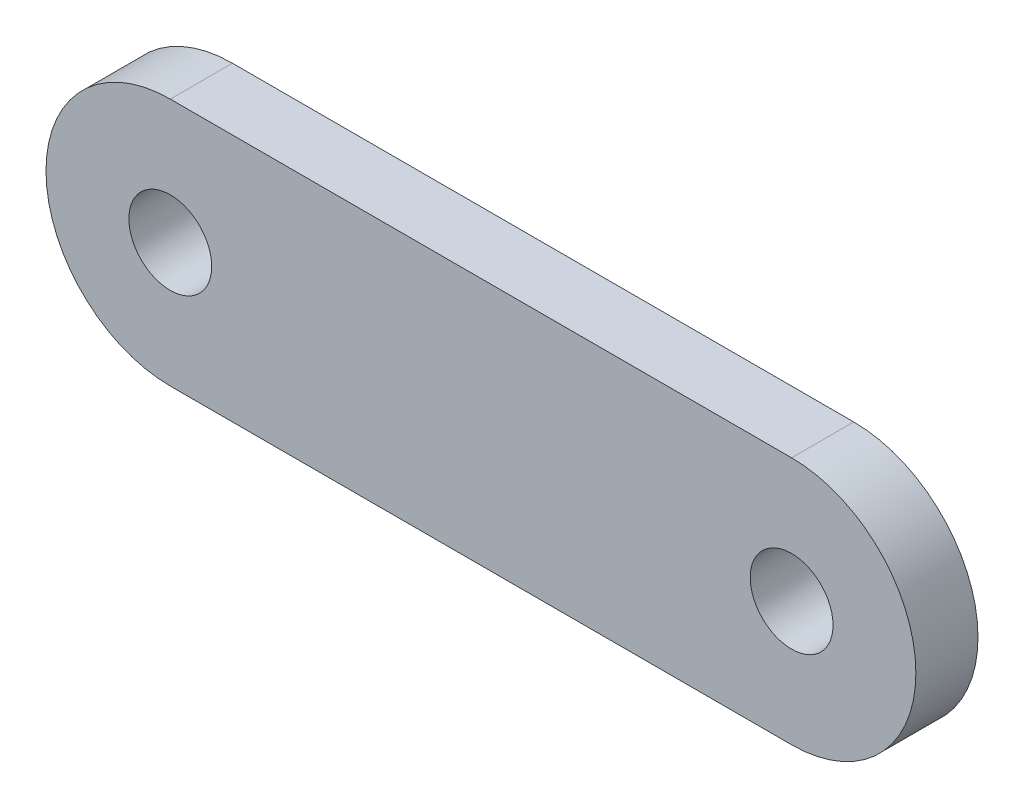
SolidWorks part; units mm, degrees
ref_plane "Front Plane" through (0, 0, 0) normal (0, 0, 1) x (1, 0, 0)
ref_plane "Top Plane" through (0, 0, 0) normal (0, 1, 0) x (1, 0, 0)
ref_plane "Right Plane" through (0, 0, 0) normal (1, 0, 0) x (0, 0, -1)
sketch "Sketch1" plane through (0, 0, 0) normal (0, 0, 1) x (1, 0, 0)
  line L0 (-35.3127, 0) -> (-5.3127, 0) construction
  line L1 (-35.3127, 6) -> (-5.3127, 6)
  line L2 (-35.3127, -6) -> (-5.3127, -6)
  arc A0 (-35.3127, 6) -> (-35.3127, -6) centre (-35.3127, 0) ccw
  arc A1 (-5.3127, -6) -> (-5.3127, 6) centre (-5.3127, 0) ccw
  circle A2 centre (-35.3127, 0) radius 2
  circle A3 centre (-5.3127, 0) radius 2
  point P3 (-20.3127, 0)
  dimension "D3" = 4
  dimension "D4" = 4
  dimension "D1" = 30
  dimension "D2" = 12
extrude "Boss-Extrude3" add sketch "Sketch1" along normal blind 3
